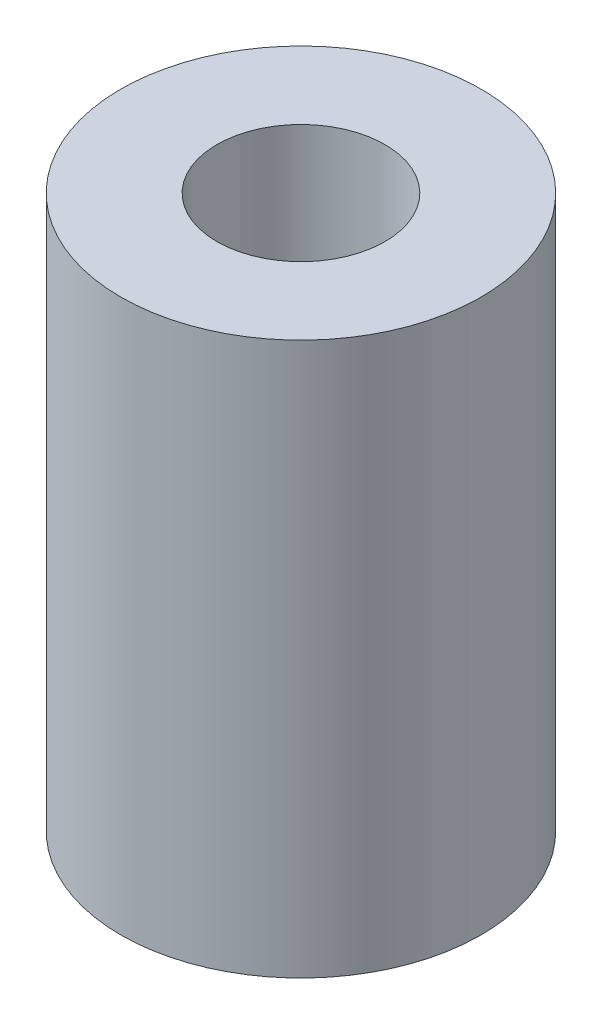
SolidWorks part; units mm, degrees
ref_plane "Front Plane" through (0, 0, 0) normal (0, 0, 1) x (1, 0, 0)
ref_plane "Top Plane" through (0, 0, 0) normal (0, 1, 0) x (1, 0, 0)
ref_plane "Right Plane" through (0, 0, 0) normal (1, 0, 0) x (0, 0, -1)
sketch "Sketch2" plane through (0, 0, 0) normal (0, 1, 0) x (1, 0, 0)
  circle A0 centre (0, 0) radius 15
  circle A1 centre (0, 0) radius 7
  dimension "D1" = 30
  dimension "D2" = 14
extrude "Boss-Extrude2" add sketch "Sketch2" along normal blind 46
